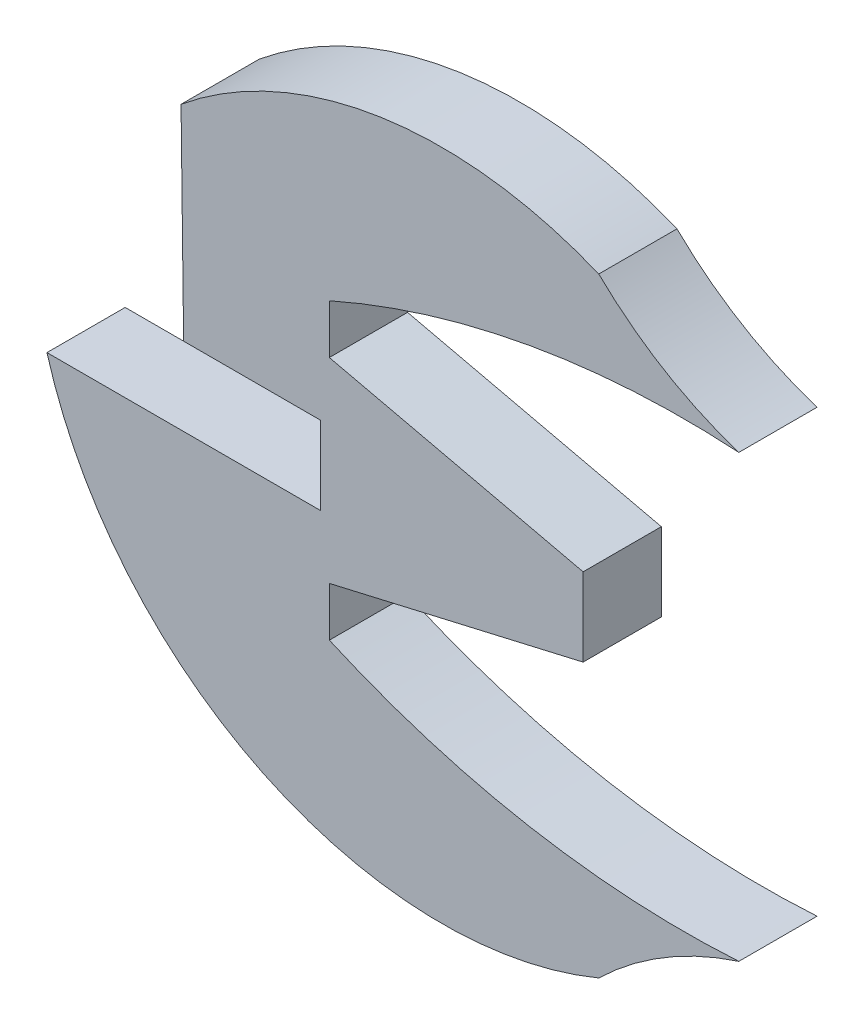
SolidWorks part; units mm, degrees
ref_plane "Front Plane" through (0, 0, 0) normal (0, 0, 1) x (1, 0, 0)
ref_plane "Top Plane" through (0, 0, 0) normal (0, 1, 0) x (1, 0, 0)
ref_plane "Right Plane" through (0, 0, 0) normal (1, 0, 0) x (0, 0, -1)
sketch "Sketch1" plane through (0, 0, 0) normal (0, 0, 1) x (1, 0, 0)
  line L0 (41.6848, 0) -> (41.6848, -1.524)
  line L1 (41.6848, -1.524) -> (36.358, -1.524)
  line L2 (41.8608, -2.6676) -> (41.8608, -3.6262)
  line L3 (41.8608, -2.6676) -> (46.8062, -1.524)
  line L4 (46.8062, -1.524) -> (46.8062, 0)
  line L5 (46.8062, -0.762) -> (54.7931, -0.762) construction
  line L6 (41.8608, 1.1436) -> (41.8608, 2.1022)
  line L7 (41.8608, 1.1436) -> (46.8062, 0)
  line L8 (41.6848, 0) -> (39.0214, 0)
  line L9 (38.9711, 3.9729) -> (39.0214, 0)
  arc A0 (41.8608, -3.6262) -> (49.8407, -5.0565) centre (48.7735, 11.9651) ccw
  arc A1 (49.8407, -5.0565) -> (47.1111, -6.7023) centre (52.0029, -11.7291) ccw
  arc A2 (47.1111, -6.7023) -> (36.358, -1.524) centre (44.046, 0.6868) cw
  arc A3 (49.8407, 3.5325) -> (47.1111, 5.1783) centre (52.0029, 10.2051) cw
  arc A4 (41.8608, 2.1022) -> (49.8407, 3.5325) centre (48.7735, -13.4891) cw
  arc A5 (47.1111, 5.1783) -> (38.9711, 3.9729) centre (44.046, -2.2108) ccw
extrude "Boss-Extrude1" add sketch "Sketch1" along normal blind 1.524
